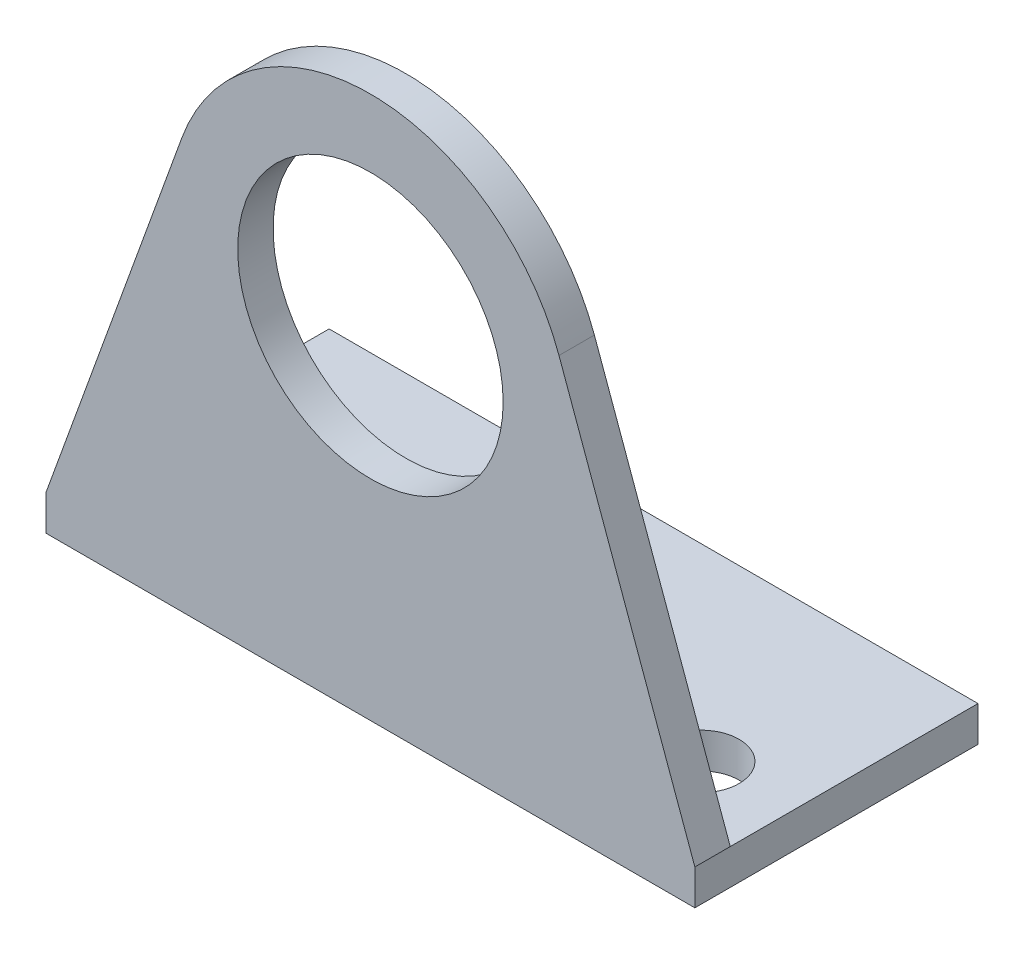
SolidWorks part; units mm, degrees
ref_plane "前视基准面" through (0, 0, 0) normal (0, 0, 1) x (1, 0, 0)
ref_plane "上视基准面" through (0, 0, 0) normal (0, 1, 0) x (1, 0, 0)
ref_plane "右视基准面" through (0, 0, 0) normal (1, 0, 0) x (0, 0, -1)
other "Configuration Table"
sketch "草图1" plane through (0, 0, 0) normal (0, 1, 0) x (1, 0, 0)
  line L0 (47.5, 8) -> (7.5, 8) construction
  line L1 (0, 0) -> (55, 0)
  line L2 (0, 0) -> (0, 24)
  line L3 (0, 24) -> (55, 24)
  line L4 (55, 0) -> (55, 24)
  circle A0 centre (47.5, 8) radius 3.25
  circle A1 centre (7.5, 8) radius 3.25
  dimension "D5" = 6.5
  dimension "D1" = 55
  dimension "D2" = 24
  dimension "D3" = 40
  dimension "D4" = 7.5
  dimension "D6" = 8
extrude "凸台-拉伸1" add sketch "草图1" along normal blind 3
sketch "草图3" plane through (0, 0, 0) normal (0, 0, 1) x (1, 0, 0)
  line L0 (0, 3) -> (11.5165, 34.7903)
  line L1 (55, 3) -> (43.4835, 34.7903)
  line L2 (0, 3) -> (55, 3) construction
  line L3 (0, 3) -> (55, 3)
  arc A0 (11.5165, 34.7903) -> (43.4835, 34.7903) centre (27.5, 29) cw
  circle A1 centre (27.5, 29) radius 11.25
  point P7 (27.5, 46)
  dimension "D3" = 22.5
  dimension "D1" = 43
  dimension "D2" = 26
extrude "凸台-拉伸2" add sketch "草图3" against normal blind 3
